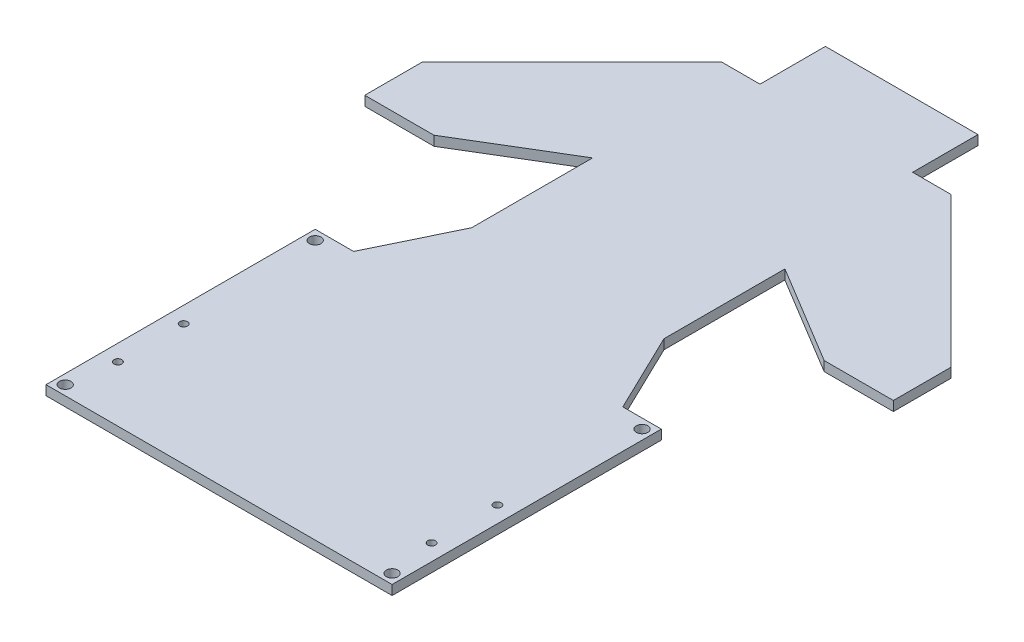
SolidWorks part; units mm, degrees
ref_plane "Front Plane" through (0, 0, 0) normal (0, 0, 1) x (1, 0, 0)
ref_plane "Top Plane" through (0, 0, 0) normal (0, 1, 0) x (1, 0, 0)
ref_plane "Right Plane" through (0, 0, 0) normal (1, 0, 0) x (0, 0, -1)
sketch "Sketch1" plane through (0, 0, 0) normal (0, 1, 0) x (1, 0, 0)
  line L7 (-36.3881, -49.0618) -> (-46.3881, -49.0618)
  line L8 (-46.3881, -49.0618) -> (-46.3881, -119.0618)
  line L9 (-46.3881, -119.0618) -> (43.6119, -119.0618)
  line L10 (43.6119, -119.0618) -> (43.6119, -49.0618)
  line L11 (43.6119, -49.0618) -> (33.6119, -49.0618)
  line L32 (-36.3881, -49.0618) -> (-26.3881, -28.3689)
  line L34 (23.6119, -28.3689) -> (33.6119, -49.0618)
  line L37 (-52.125, -12.4356) -> (-70.125, -12.4356)
  line L38 (-70.125, -12.4356) -> (-70.125, 2.5644)
  line L39 (-70.125, 2.5644) -> (-31.2308, 41.4519)
  line L40 (-31.2308, 41.4519) -> (-21.2308, 41.4519)
  line L41 (28.4572, 41.4519) -> (67.3447, 2.5576)
  line L42 (67.3447, 2.5576) -> (67.3447, -12.4424)
  line L43 (67.3447, -12.4424) -> (49.3447, -12.4424)
  line L46 (-21.2308, 41.4519) -> (-21.2308, 58.4519)
  line L47 (-21.2308, 58.4519) -> (18.4572, 58.4519)
  line L48 (18.4572, 58.4519) -> (18.4572, 41.4519)
  line L49 (18.4572, 41.4519) -> (28.4572, 41.4519)
  line L55 (-26.3881, -28.3689) -> (-26.3881, 3.0868)
  line L56 (-26.3881, 3.0868) -> (-52.125, -12.4356)
  line L57 (23.6119, -28.3689) -> (23.6119, 3.0868)
  line L58 (23.6119, 3.0868) -> (49.3447, -12.4424)
  circle A0 centre (41.1119, -51.5618) radius 1.5
  circle A1 centre (-43.8881, -51.5618) radius 1.5
  circle A2 centre (-43.8881, -116.5618) radius 1.5
  circle A3 centre (41.1119, -116.5618) radius 1.5
  dimension "D12" = 3
  dimension "D13" = 3
  dimension "D18" = 3
  dimension "D19" = 3
  dimension "D3" = 50
  dimension "D4" = 31.4557
  dimension "D5" = 15
  dimension "D6" = 18
  dimension "D7" = 55
  dimension "D8" = 70
  dimension "D9" = 90
  dimension "D10" = 10
  dimension "D11" = 10
  dimension "D14" = 2.5
  dimension "D15" = 2.5
  dimension "D16" = 2.5
  dimension "D17" = 2.5
  dimension "D20" = 2.5
  dimension "D21" = 2.5
  dimension "D22" = 2.5
  dimension "D23" = 2.5
  dimension "D24" = 115.793
  dimension "D26" = 17
extrude "Boss-Extrude1" add sketch "Sketch1" against normal blind 2.5
sketch "Sketch2" plane through (0, 0, 0) normal (0, 1, 0) x (1, 0, 0)
  line L0 (-46.3881, -49.0618) -> (-46.3881, -119.0618) construction
  line L1 (-46.3881, -119.0618) -> (43.6119, -119.0618) construction
  circle A0 centre (-42.1881, -87.4618) radius 1
  circle A1 centre (-42.1881, -104.5618) radius 1
  dimension "D1" = 2
  dimension "D2" = 2
  dimension "D3" = 17.1
  dimension "D4" = 4.2
  dimension "D5" = 4.2
  dimension "D6" = 14.5
extrude "Cut-Extrude1" cut sketch "Sketch2" against normal blind 10
sketch "Sketch3" plane through (0, 0, 0) normal (0, 1, 0) x (1, 0, 0)
  line L0 (-46.3881, -119.0618) -> (43.6119, -119.0618) construction
  line L2 (43.6119, -119.0618) -> (43.6119, -49.0618) construction
  circle A0 centre (39.3819, -87.4618) radius 1
  circle A1 centre (39.3819, -104.5618) radius 1
  dimension "D1" = 2
  dimension "D2" = 4.23
  dimension "D3" = 4.23
  dimension "D4" = 31.6
extrude "Cut-Extrude2" cut sketch "Sketch3" against normal blind 10
